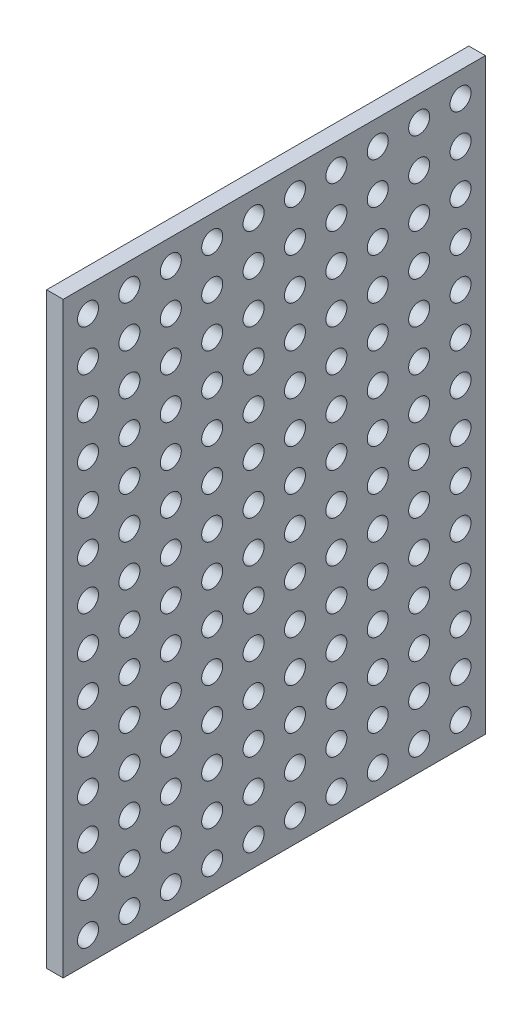
SolidWorks part; units mm, degrees
ref_plane "Front Plane" through (0, 0, 0) normal (0, 0, 1) x (1, 0, 0)
ref_plane "Top Plane" through (0, 0, 0) normal (0, 1, 0) x (1, 0, 0)
ref_plane "Right Plane" through (0, 0, 0) normal (1, 0, 0) x (0, 0, -1)
sketch "Sketch1" plane through (0, 0, 0) normal (1, 0, 0) x (0, 0, -1)
  line L1 (0, 0) -> (25.5, 0)
  line L2 (0, 0) -> (0, 35.5)
  line L3 (0, 35.5) -> (25.5, 35.5)
  line L4 (25.5, 0) -> (25.5, 35.5)
  circle A0 centre (1.5, 34) radius 0.635
  circle A1 centre (4, 34) radius 0.635
  circle A2 centre (6.5, 34) radius 0.635
  circle A3 centre (9, 34) radius 0.635
  circle A4 centre (11.5, 34) radius 0.635
  circle A5 centre (14, 34) radius 0.635
  circle A6 centre (16.5, 34) radius 0.635
  circle A7 centre (19, 34) radius 0.635
  circle A8 centre (21.5, 34) radius 0.635
  circle A9 centre (24, 34) radius 0.635
  circle A10 centre (4, 31.5) radius 0.635
  circle A11 centre (6.5, 31.5) radius 0.635
  circle A12 centre (9, 31.5) radius 0.635
  circle A13 centre (11.5, 31.5) radius 0.635
  circle A14 centre (14, 31.5) radius 0.635
  circle A15 centre (16.5, 31.5) radius 0.635
  circle A16 centre (19, 31.5) radius 0.635
  circle A17 centre (21.5, 31.5) radius 0.635
  circle A18 centre (24, 31.5) radius 0.635
  circle A19 centre (4, 29) radius 0.635
  circle A20 centre (6.5, 29) radius 0.635
  circle A21 centre (9, 29) radius 0.635
  circle A22 centre (11.5, 29) radius 0.635
  circle A23 centre (14, 29) radius 0.635
  circle A24 centre (16.5, 29) radius 0.635
  circle A25 centre (19, 29) radius 0.635
  circle A26 centre (21.5, 29) radius 0.635
  circle A27 centre (24, 29) radius 0.635
  circle A28 centre (4, 26.5) radius 0.635
  circle A29 centre (6.5, 26.5) radius 0.635
  circle A30 centre (9, 26.5) radius 0.635
  circle A31 centre (11.5, 26.5) radius 0.635
  circle A32 centre (14, 26.5) radius 0.635
  circle A33 centre (16.5, 26.5) radius 0.635
  circle A34 centre (19, 26.5) radius 0.635
  circle A35 centre (21.5, 26.5) radius 0.635
  circle A36 centre (24, 26.5) radius 0.635
  circle A37 centre (4, 24) radius 0.635
  circle A38 centre (6.5, 24) radius 0.635
  circle A39 centre (9, 24) radius 0.635
  circle A40 centre (11.5, 24) radius 0.635
  circle A41 centre (14, 24) radius 0.635
  circle A42 centre (16.5, 24) radius 0.635
  circle A43 centre (19, 24) radius 0.635
  circle A44 centre (21.5, 24) radius 0.635
  circle A45 centre (24, 24) radius 0.635
  circle A46 centre (4, 21.5) radius 0.635
  circle A47 centre (6.5, 21.5) radius 0.635
  circle A48 centre (9, 21.5) radius 0.635
  circle A49 centre (11.5, 21.5) radius 0.635
  circle A50 centre (14, 21.5) radius 0.635
  circle A51 centre (16.5, 21.5) radius 0.635
  circle A52 centre (19, 21.5) radius 0.635
  circle A53 centre (21.5, 21.5) radius 0.635
  circle A54 centre (24, 21.5) radius 0.635
  circle A55 centre (4, 19) radius 0.635
  circle A56 centre (6.5, 19) radius 0.635
  circle A57 centre (9, 19) radius 0.635
  circle A58 centre (11.5, 19) radius 0.635
  circle A59 centre (14, 19) radius 0.635
  circle A60 centre (16.5, 19) radius 0.635
  circle A61 centre (19, 19) radius 0.635
  circle A62 centre (21.5, 19) radius 0.635
  circle A63 centre (24, 19) radius 0.635
  circle A64 centre (4, 16.5) radius 0.635
  circle A65 centre (6.5, 16.5) radius 0.635
  circle A66 centre (9, 16.5) radius 0.635
  circle A67 centre (11.5, 16.5) radius 0.635
  circle A68 centre (14, 16.5) radius 0.635
  circle A69 centre (16.5, 16.5) radius 0.635
  circle A70 centre (19, 16.5) radius 0.635
  circle A71 centre (21.5, 16.5) radius 0.635
  circle A72 centre (24, 16.5) radius 0.635
  circle A73 centre (4, 14) radius 0.635
  circle A74 centre (6.5, 14) radius 0.635
  circle A75 centre (9, 14) radius 0.635
  circle A76 centre (11.5, 14) radius 0.635
  circle A77 centre (14, 14) radius 0.635
  circle A78 centre (16.5, 14) radius 0.635
  circle A79 centre (19, 14) radius 0.635
  circle A80 centre (21.5, 14) radius 0.635
  circle A81 centre (24, 14) radius 0.635
  circle A82 centre (4, 11.5) radius 0.635
  circle A83 centre (6.5, 11.5) radius 0.635
  circle A84 centre (9, 11.5) radius 0.635
  circle A85 centre (11.5, 11.5) radius 0.635
  circle A86 centre (14, 11.5) radius 0.635
  circle A87 centre (16.5, 11.5) radius 0.635
  circle A88 centre (19, 11.5) radius 0.635
  circle A89 centre (21.5, 11.5) radius 0.635
  circle A90 centre (24, 11.5) radius 0.635
  circle A91 centre (4, 9) radius 0.635
  circle A92 centre (6.5, 9) radius 0.635
  circle A93 centre (9, 9) radius 0.635
  circle A94 centre (11.5, 9) radius 0.635
  circle A95 centre (14, 9) radius 0.635
  circle A96 centre (16.5, 9) radius 0.635
  circle A97 centre (19, 9) radius 0.635
  circle A98 centre (21.5, 9) radius 0.635
  circle A99 centre (24, 9) radius 0.635
  circle A100 centre (4, 6.5) radius 0.635
  circle A101 centre (6.5, 6.5) radius 0.635
  circle A102 centre (9, 6.5) radius 0.635
  circle A103 centre (11.5, 6.5) radius 0.635
  circle A104 centre (14, 6.5) radius 0.635
  circle A105 centre (16.5, 6.5) radius 0.635
  circle A106 centre (19, 6.5) radius 0.635
  circle A107 centre (21.5, 6.5) radius 0.635
  circle A108 centre (24, 6.5) radius 0.635
  circle A109 centre (1.5, 31.5) radius 0.635
  circle A110 centre (1.5, 29) radius 0.635
  circle A111 centre (1.5, 26.5) radius 0.635
  circle A112 centre (1.5, 24) radius 0.635
  circle A113 centre (1.5, 21.5) radius 0.635
  circle A114 centre (1.5, 19) radius 0.635
  circle A115 centre (1.5, 16.5) radius 0.635
  circle A116 centre (1.5, 14) radius 0.635
  circle A117 centre (1.5, 11.5) radius 0.635
  circle A118 centre (1.5, 9) radius 0.635
  circle A119 centre (1.5, 6.5) radius 0.635
  circle A120 centre (1.5, 4) radius 0.635
  circle A121 centre (4, 4) radius 0.635
  circle A122 centre (6.5, 4) radius 0.635
  circle A123 centre (9, 4) radius 0.635
  circle A124 centre (11.5, 4) radius 0.635
  circle A125 centre (14, 4) radius 0.635
  circle A126 centre (16.5, 4) radius 0.635
  circle A127 centre (19, 4) radius 0.635
  circle A128 centre (21.5, 4) radius 0.635
  circle A129 centre (24, 4) radius 0.635
  circle A130 centre (1.5, 1.5) radius 0.635
  circle A131 centre (4, 1.5) radius 0.635
  circle A132 centre (6.5, 1.5) radius 0.635
  circle A133 centre (9, 1.5) radius 0.635
  circle A134 centre (11.5, 1.5) radius 0.635
  circle A135 centre (14, 1.5) radius 0.635
  circle A136 centre (16.5, 1.5) radius 0.635
  circle A137 centre (19, 1.5) radius 0.635
  circle A138 centre (21.5, 1.5) radius 0.635
  circle A139 centre (24, 1.5) radius 0.635
  dimension "D2" = 1.27
  dimension "D1" = 1.5
  dimension "D7" = 1.5
  dimension "D5" = 1.5
  dimension "D6" = 1.5
  dimension "D3" = 10
  dimension "D4" = 14
extrude "Boss-Extrude1" add sketch "Sketch1" along normal blind 1
